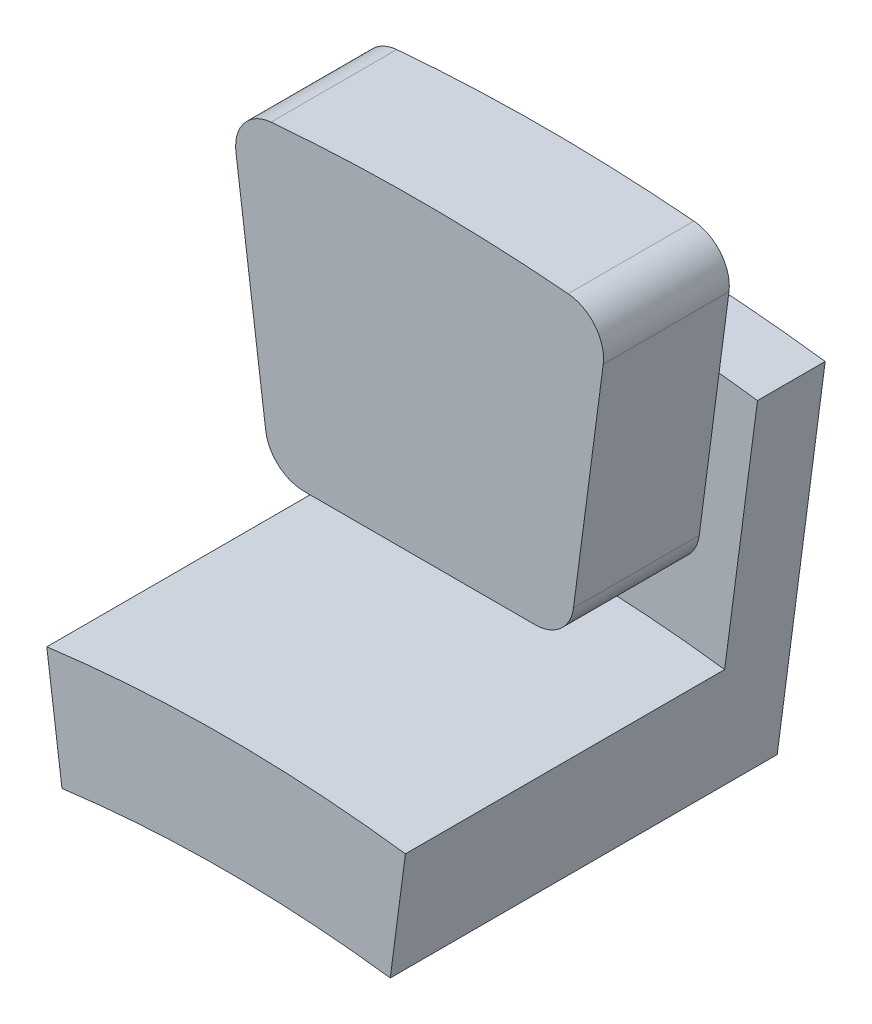
SolidWorks part; units mm, degrees
material "6061-T6 (SS)"
ref_plane "Front Plane" through (0, 0, 0) normal (0, 0, 1) x (1, 0, 0)
ref_plane "Top Plane" through (0, 0, 0) normal (0, 1, 0) x (1, 0, 0)
ref_plane "Right Plane" through (0, 0, 0) normal (1, 0, 0) x (0, 0, -1)
sketch "Sketch1" plane through (0, 0, 0) normal (0, 0, 1) x (1, 0, 0)
  line L0 (-8.9782, 83.5188) -> (-7.725, 74)
  line L1 (8.9782, 83.5188) -> (7.725, 74)
  line L2 (8.9782, 83.5188) -> (9.7616, 89.4691)
  line L3 (-8.9782, 83.5188) -> (-9.7616, 89.4691)
  line L4 (7.725, 74) -> (-7.725, 74) construction
  line L5 (0, 0) -> (-10.9642, 83.2814) construction
  line L6 (0, 0) -> (10.9642, 83.2814) construction
  line L7 (10.9642, 83.2814) -> (-10.9642, 83.2814) construction
  line L8 (0, 83.2814) -> (0, 0) construction
  line L9 (8.4842, 64.4439) -> (9.7114, 73.7656)
  line L10 (-8.4842, 64.4439) -> (-9.7114, 73.7656)
  circle A0 centre (0, 0) radius 84 construction
  arc A1 (-9.7616, 89.4691) -> (9.7616, 89.4691) centre (0, 0) cw
  circle A2 centre (0, 0) radius 90 construction
  arc A3 (-8.4842, 64.4439) -> (8.4842, 64.4439) centre (0, 0) cw
  arc A4 (7.725, 74) -> (9.7114, 73.7656) centre (0, 0) cw
  arc A5 (-7.725, 74) -> (-9.7114, 73.7656) centre (0, 0) ccw
  arc A6 (-9.2674, 70.3926) -> (9.2674, 70.3926) centre (0, 0) cw construction
  point P14 (0, 90)
  point P24 (-9.3482, 71.0064)
  dimension "D6" = 65
  dimension "D1" = 15
  dimension "D2" = 4
  dimension "D3" = 16
  dimension "D4" = 19.5231
  dimension "D5" = 6
extrude "Boss-Extrude1" add sketch "Sketch1" along normal up to surface (20 mm away)
sketch "Sketch2" plane through (0, 0, 0) normal (0, 0, -1) x (-1, 0, 0)
  line L0 (-9.7616, 89.4691) -> (-8.9782, 83.5188)
  line L1 (9.7616, 89.4691) -> (8.9782, 83.5188)
  line L2 (9.7616, 89.4691) -> (7.725, 74) construction
  line L3 (-7.725, 74) -> (-9.7616, 89.4691) construction
  arc A0 (9.7616, 89.4691) -> (-9.7616, 89.4691) centre (0, 0) ccw construction
  arc A1 (9.7616, 89.4691) -> (-9.7616, 89.4691) centre (0, 0) ccw
  circle A2 centre (0, 0) radius 84 construction
  arc A3 (8.9782, 83.5188) -> (-8.9782, 83.5188) centre (0, 0) ccw
  point P12 (-8.7171, 81.5353)
extrude "Cut-Extrude1" cut sketch "Sketch2" against normal up to surface (3.5 mm away)
sketch "Sketch3" plane through (0, 0, 20) normal (0, 0, 1) x (1, 0, 0)
  line L0 (7.725, 74) -> (-7.725, 74) construction
  line L1 (7.725, 74) -> (-7.725, 74)
  line L2 (9.2674, 70.3926) -> (9.7114, 73.7656)
  line L3 (-9.2674, 70.3926) -> (-9.7114, 73.7656)
  arc A0 (9.2674, 70.3926) -> (-9.2674, 70.3926) centre (0, 0) ccw construction
  arc A1 (9.2674, 70.3926) -> (-9.2674, 70.3926) centre (0, 0) ccw
  arc A2 (-7.725, 74) -> (-9.7114, 73.7656) centre (0, 0) ccw construction
  arc A3 (9.7114, 73.7656) -> (7.725, 74) centre (0, 0) ccw construction
  arc A4 (-7.725, 74) -> (-9.7114, 73.7656) centre (0, 0) ccw
  arc A5 (9.7114, 73.7656) -> (7.725, 74) centre (0, 0) ccw
extrude "Cut-Extrude2" cut sketch "Sketch3" against normal up to surface (16.5 mm away)
sketch "Sketch4" plane through (0, 0, 20) normal (0, 0, 1) x (1, 0, 0)
  line L3 (-7.725, 74) -> (7.725, 74)
  line L4 (7.725, 74) -> (9.7616, 89.4691)
  line L5 (-9.7616, 89.4691) -> (-7.725, 74)
  line L6 (-7.725, 74) -> (7.725, 74)
  line L7 (7.725, 74) -> (9.7616, 89.4691)
  line L8 (-9.7616, 89.4691) -> (-7.725, 74)
  arc A1 (9.7616, 89.4691) -> (-9.7616, 89.4691) centre (0, 0) ccw
  arc A2 (9.7616, 89.4691) -> (-9.7616, 89.4691) centre (0, 0) ccw
  dimension "D1" = 0
extrude "Cut-Extrude3" cut sketch "Sketch4" against normal offset from surface (10 mm away) 10
sketch "Sketch5" plane through (0, 0, 3.5) normal (0, 0, 1) x (1, 0, 0)
  line L0 (9.7114, 73.7656) -> (10.9642, 83.2814)
  line L1 (-9.7114, 73.7656) -> (-10.9642, 83.2814)
  line L2 (-7.725, 74) -> (-8.9782, 83.5188)
  line L3 (7.725, 74) -> (8.9782, 83.5188)
  line L4 (9.7616, 89.4691) -> (7.725, 74) construction
  line L5 (9.7114, 73.7656) -> (9.2674, 70.3926) construction
  line L6 (-7.725, 74) -> (-9.7616, 89.4691) construction
  line L7 (-9.2674, 70.3926) -> (-9.7114, 73.7656) construction
  circle A0 centre (0, 0) radius 84 construction
  arc A1 (10.9642, 83.2814) -> (8.9782, 83.5188) centre (0, 0) ccw
  arc A2 (-8.9782, 83.5188) -> (-10.9642, 83.2814) centre (0, 0) ccw
  arc A3 (9.7114, 73.7656) -> (7.725, 74) centre (0, 0) ccw construction
  arc A4 (9.7114, 73.7656) -> (7.725, 74) centre (0, 0) ccw
  arc A5 (-7.725, 74) -> (-9.7114, 73.7656) centre (0, 0) ccw construction
  arc A6 (-7.725, 74) -> (-9.7114, 73.7656) centre (0, 0) ccw
extrude "Boss-Extrude2" add sketch "Sketch5" against normal up to surface (3.5 mm away) up to face at (0, 74.0634, 0)
fillet "Fillet1" radius 2 4 edges at (-9.7616, 89.4691, 6.75) (9.7616, 89.4691, 6.75) (-7.725, 74, 6.75) (7.725, 74, 6.75)
